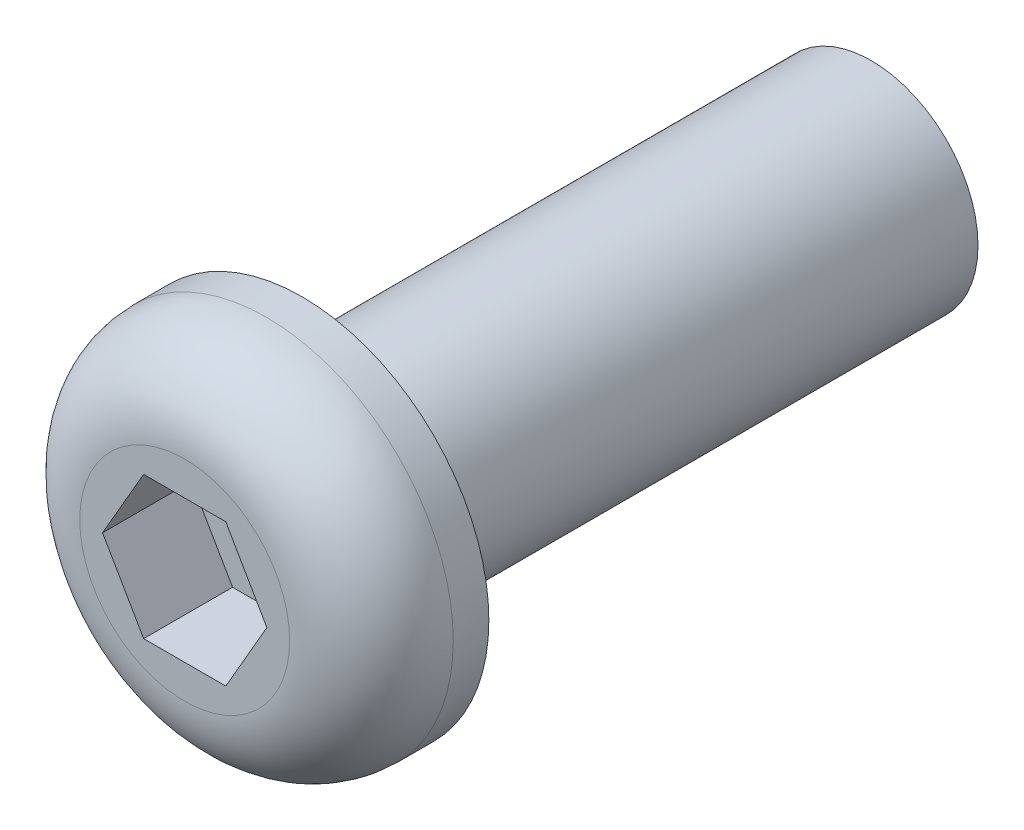
SolidWorks part; units mm, degrees
material "AISI 304"
ref_plane "Front Plane" through (0, 0, 0) normal (0, 0, 1) x (1, 0, 0)
ref_plane "Top Plane" through (0, 0, 0) normal (0, 1, 0) x (1, 0, 0)
ref_plane "Right Plane" through (0, 0, 0) normal (1, 0, 0) x (0, 0, -1)
sketch "Sketch1" plane through (0, 0, 0) normal (0, 0, 1) x (1, 0, 0)
  circle A0 centre (0, 0) radius 3
  dimension "D1" = 6
extrude "Extrude1" add sketch "Sketch1" against normal blind 16
sketch "Sketch2" plane through (0, 0, 0) normal (1, 0, 0) x (0, 0, -1)
  line L0 (0, 0) -> (-10.9859, 0) construction
  line L1 (0, 0) -> (0, 5.25)
  line L2 (0, 5.25) -> (-1, 5.25)
  line L3 (-3.3, 0) -> (-3.3, 2.95)
  line L4 (0, 0) -> (-3.3, 0)
  arc A0 (-3.3, 2.95) -> (-1, 5.25) centre (-1, 2.95) cw
  dimension "D1" = 3.3
  dimension "D2" = 10.5
  dimension "D3" = 1
revolve "Revolve1" add sketch "Sketch2" angle 360 about L0
sketch "Sketch3" plane through (0, 0, 3.3) normal (0, 0, 1) x (1, 0, 0)
  line L1 (-1.1547, 2) -> (-2.3094, 0)
  line L2 (-2.3094, 0) -> (-1.1547, -2)
  line L3 (-1.1547, -2) -> (1.1547, -2)
  line L4 (1.1547, -2) -> (2.3094, 0)
  line L5 (2.3094, 0) -> (1.1547, 2)
  line L6 (1.1547, 2) -> (-1.1547, 2)
  circle A0 centre (0, 0) radius 2 construction
  dimension "D1" = 4
extrude "Cut-Extrude1" cut sketch "Sketch3" against normal blind 2.5
